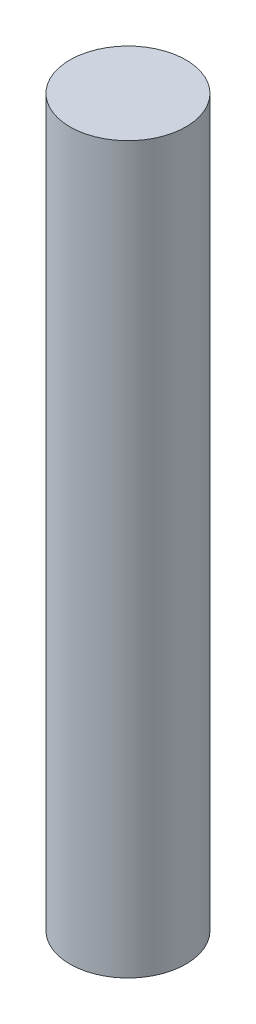
SolidWorks part; units mm, degrees
ref_plane "Front Plane" through (0, 0, 0) normal (0, 0, 1) x (1, 0, 0)
ref_plane "Top Plane" through (0, 0, 0) normal (0, 1, 0) x (1, 0, 0)
ref_plane "Right Plane" through (0, 0, 0) normal (1, 0, 0) x (0, 0, -1)
sketch "Sketch1" plane through (0, 0, 0) normal (0, 1, 0) x (1, 0, 0)
  circle A0 centre (0, 0) radius 4.572
  dimension "D1" = 9.144
extrude "Boss-Extrude1" add sketch "Sketch1" along normal blind 57.15
